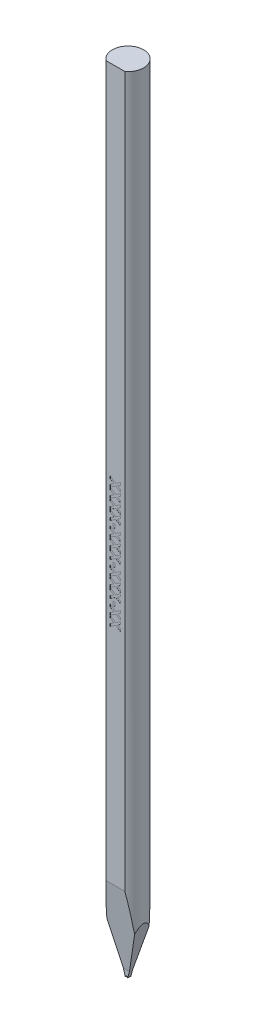
SolidWorks part; units mm, degrees
ref_plane "Ebene vorne" through (0, 0, 0) normal (0, 0, 1) x (1, 0, 0)
ref_plane "Ebene oben" through (0, 0, 0) normal (0, 1, 0) x (1, 0, 0)
ref_plane "Ebene rechts" through (0, 0, 0) normal (1, 0, 0) x (0, 0, -1)
sketch "sketch_TL_cutting" plane through (0, 0, 0) normal (0, 1, 0) x (1, 0, 0)
  circle A0 centre (0, 0) radius 1.4986
extrude "TL_cutting" add sketch "sketch_TL_cutting" along normal blind 75.9968
sketch "sketch_TDF_grinding" plane through (0, 0, 0) normal (0, 1, 0) x (1, 0, 0)
  line L0 (0, 0) -> (0, -1.2014) construction
  line L1 (-1.5086, -4.2186) -> (1.5086, -4.2186)
  line L2 (-1.5086, -4.2186) -> (-1.5086, -1.2014)
  line L3 (-1.5086, -1.2014) -> (1.5086, -1.2014)
  line L4 (1.5086, -4.2186) -> (1.5086, -1.2014)
  circle A1 centre (0, 0) radius 1.4986 construction
  point P9 (0, -4.2186)
  dimension "TD_2Offset_X" = 3.0172
  dimension "TD_2Offset_Z" = 3.0172
extrude "TDF_grinding" cut sketch "sketch_TDF_grinding" along normal through all
sketch "sketch_engraving" plane through (0, 0, 1.2014) normal (0, 0, 1) x (1, 0, 0)
  line L0 (0.8958, 75.9968) -> (-0.8958, 75.9968) construction
  line L6 (-0.8958, 0) -> (0.8958, 0) construction
  line L7 (0, 0) -> (0, 41.7982) construction
  line L8 (-0.5, 41.7982) -> (-0.5, 0) construction
  text T0 "XXXX-XXX-XXX-XX" font "Arial" height 1
  dimension "D2" = 0.5
  dimension "EngravingStart" = 34.1986
extrude "engraving" cut sketch "sketch_engraving" against normal blind 0.005
sketch "sketch_VW_VR_grinding" plane through (0, 0, 0) normal (0, 0, 1) x (1, 0, 0)
  line L0 (-1.4936, -0.01) -> (-1.4936, 0.5946)
  line L1 (1.4936, -0.01) -> (1.4936, 0.5946)
  line L2 (-1.4936, 0) -> (1.4936, 0) construction
  line L3 (-1.5086, 0.5996) -> (-1.4986, 0.5996)
  line L4 (1.4986, 0.5996) -> (1.5086, 0.5996)
  line L5 (-1.5086, 0.5996) -> (-1.5086, -0.01)
  line L6 (-1.5086, -0.01) -> (-1.4936, -0.01)
  line L7 (1.4936, -0.01) -> (1.5086, -0.01)
  line L8 (1.5086, -0.01) -> (1.5086, 0.5996)
  line L9 (-1.4986, 0.5996) -> (-1.4986, 0.5946) construction
  line L10 (-1.4936, 0.5946) -> (-1.4986, 0.5946) construction
  line L11 (1.4936, 0.5946) -> (1.4986, 0.5946) construction
  line L12 (1.4986, 0.5996) -> (1.4986, 0.5946) construction
  arc A0 (-1.4986, 0.5996) -> (-1.4936, 0.5946) centre (-1.4986, 0.5946) cw
  arc A2 (1.4936, 0.5946) -> (1.4986, 0.5996) centre (1.4986, 0.5946) cw
  dimension "D1" = 0.01
  dimension "D4" = 3.0172
extrude "VW_VR_grinding" cut sketch "sketch_VW_VR_grinding" against normal blind 1.5086 and the other way blind 1.5086
sketch "sketch_ISA_grinding" plane through (0, 0, 0) normal (0, 0, 1) x (1, 0, 0)
  line L0 (-0.1245, 0) -> (-1.5086, 5.1657)
  line L4 (1.5086, 5.1657) -> (0.1245, 0)
  line L5 (0.1245, 0) -> (-0.1245, 0)
  line L6 (0, 0) -> (0, 30.49) construction
  line L7 (-1.5086, 5.1657) -> (-1.5086, -0.01)
  line L12 (-1.5086, -0.01) -> (1.5086, -0.01)
  line L13 (1.5086, -0.01) -> (1.5086, 5.1657)
  dimension "ISA" = 30
  dimension "TD_2Offset" = 3.0172
  dimension "Offset" = 0.01
extrude "ISA_grinding" cut sketch "sketch_ISA_grinding" against normal blind 1.5086 and the other way blind 1.5086
sketch "sketch_pre_FRX_BRX" plane through (0, 0, 0) normal (1, 0, 0) x (0, 0, -1)
  line L0 (1.4986, -0.01) -> (1.4986, 3.9152) construction
  line L1 (-1.2014, -0.01) -> (-1.2014, 0.5996) construction
  line L2 (-0.1499, -0.01) -> (-0.1499, 0.5996)
  line L3 (-0.1499, 0.5996) -> (-1.5086, 0.5996)
  line L4 (-1.5086, 0.5996) -> (-1.5086, -0.01)
  line L5 (-1.5086, -0.01) -> (-0.1499, -0.01)
  line L6 (0.1499, -0.01) -> (0.1499, 0.5996)
  line L7 (0.1499, 0.5996) -> (1.5086, 0.5996)
  line L8 (1.5086, 0.5996) -> (1.5086, -0.01)
  line L9 (1.5086, -0.01) -> (0.1499, -0.01)
  dimension "D3" = 0.01
  dimension "D4" = 0.6096
  dimension "D5" = 3.0172
  dimension "D6" = 0.2997
  dimension "D2" = 0.01
  dimension "D7" = 1.6485
extrude "pre_FRX_BRX" cut sketch "sketch_pre_FRX_BRX" against normal blind 1.5086 and the other way blind 1.5086
sketch "sketch_contour_V-Groove" plane through (0, 0, 0) normal (1, 0, 0) x (0, 0, -1)
  line L0 (-1.2014, 0.0787) -> (0, 0.0787)
  line L1 (0, 0.0787) -> (1.4986, 0.0787)
  line L2 (1.4986, -0.8411) -> (1.4986, 1.3178) construction
  line L3 (-1.2014, -0.9209) -> (-1.2014, 1.9363) construction
  line L4 (-1.2014, 0) -> (1.4986, 0) construction
  line L5 (0.1499, 0) -> (0.1499, 0.0787) construction
  line L6 (-0.1499, 0) -> (-0.1499, 0.0787) construction
  dimension "D1" = 0
ref_plane "front" through (0, 0, 1.2014) normal (0, 0, 1) x (1, 0, 0)
ref_plane "back" through (0, 0, -1.4986) normal (0, 0, 1) x (1, 0, 0)
sketch "sketch_section_V-Groove" plane through (0, 0, 1.2014) normal (0, 0, 1) x (1, 0, 0)
  line L0 (-0.6199, -0.7874) -> (-0.0212, 0.0677)
  line L2 (0.0212, 0.0677) -> (0.6199, -0.7874)
  line L3 (-0.6199, -0.7874) -> (0.6199, -0.7874)
  line L4 (0, -0.7874) -> (0, 0.0787) construction
  line L5 (-0.0686, 0) -> (0.0686, 0) construction
  arc A0 (0.0212, 0.0677) -> (-0.0212, 0.0677) centre (0, 0.0529) ccw
  dimension "GA" = 70
sweep "V-Groove_EDM" cut profiles "sketch_section_V-Groove" path "sketch_contour_V-Groove"
fillet "FR_EDM" radius 0.0381 3 edges at (0.0449, 0.0339, 0.1499) (0, 0.0787, 0.1499) (-0.0449, 0.0339, 0.1499)
fillet "BR_EDM" radius 0.0381 3 edges at (0.0449, 0.0339, -0.1499) (0, 0.0787, -0.1499) (-0.0449, 0.0339, -0.1499)
sketch "sketch_FA_BA_grinding" plane through (0, 0, 0) normal (1, 0, 0) x (0, 0, -1)
  line L2 (2.4986, 17.3218) -> (2.4986, -0.1)
  line L3 (2.4986, -0.1) -> (0.1499, -0.1)
  line L5 (0.1499, -0.1) -> (0.1499, 0.6096)
  line L6 (0.1499, 0.6096) -> (2.4986, 17.3218)
  line L7 (1.4986, -0.1) -> (1.4986, 10.2064) construction
  line L8 (-1.2014, 8.0918) -> (-1.2014, -0.1) construction
  line L9 (-3.0976, 21.5836) -> (-0.1499, 0.6096)
  line L10 (-0.1499, 0.6096) -> (-0.1499, -0.1)
  line L11 (-0.1499, -0.1) -> (-3.0976, -0.1)
  line L12 (-3.0976, -0.1) -> (-3.0976, 21.5836)
  line L13 (-0.1499, 0.6096) -> (0.1499, 0.6096) construction
  dimension "D4" = 1
  dimension "D1" = 0.1
  dimension "FA" = 8
  dimension "BA" = 8
extrude "FA_BA_grinding" cut sketch "sketch_FA_BA_grinding" against normal blind 1.5086 and the other way blind 1.5086
sketch "sketch_groove_dimensions" plane through (0, 0, 0) normal (1, 0, 0) x (0, 0, -1)
  line L0 (-0.1118, 0.0787) -> (0.1118, 0.0787)
  line L1 (-0.1499, 0) -> (-0.1499, 0.1168) construction
  line L2 (1.4986, 0) -> (1.4986, 0.4166) construction
  line L3 (0.1499, 0) -> (0.1499, 0.1168) construction
  line L4 (-1.2014, 0) -> (-1.2014, 0.3999) construction
  arc A0 (0.1118, 0.0787) -> (0.1499, 0.1168) centre (0.1118, 0.1168) ccw
  arc A1 (-0.1118, 0.0787) -> (-0.1499, 0.1168) centre (-0.1118, 0.1168) cw
equation "\"_Offset\"=0.01mm"
equation "\"TL\"=75.9968mm"
equation "\"TD\"=2.9972mm"
equation "\"TDF\"=2.70002mm"
equation "\"BA\"=8deg"
equation "\"ISA\"=30deg"
equation "\"FA\"=8deg"
equation "\"GR\"=0.0254mm"
equation "\"GA\"=70deg"
equation "\"GD\"=0.07874mm"
equation "\"FL\"=0.29972mm"
equation "\"F\"=0.22352mm"
equation "\"FX\"=1.05156mm"
equation "\"B\"=0.13716mm"
equation "\"VW\"=0mm"
equation "\"cleaned_VR\"= IIF ( \"VR\" > 0 , \"VR\" , \"E\" - \"_Offset\" )"
equation "\"cleaned_VW\"= IIF ( \"VW\" > 0 , \"VW\" , \"TD\" - \"_Offset\" )"
equation "\"back_edge\"= \"TD\" / 2 - \"X\""
equation "\"side_edge_Offset\"= \"TD\" / 2 + \"_Offset\""
equation "\"TD@sketch_TL_cutting\"=\"TD\""
equation "\"TL@TL_cutting\"=\"TL\""
equation "\"TDF@sketch_TDF_grinding\"=\"TDF\""
equation "\"TD_2Offset_X@sketch_TDF_grinding\"=\"TD\"+2*\"_Offset\""
equation "\"TD_2Offset_Z@sketch_TDF_grinding\"=\"TD\"+2*\"_Offset\""
equation "\"TL_Offset\"= \"TL\" + \"_Offset\""
equation "\"ISA@sketch_ISA_grinding\"=\"ISA\""
equation "\"W@sketch_ISA_grinding\"=\"W\""
equation "\"TD_2Offset@sketch_ISA_grinding\"=\"TD\"+2*\"_Offset\""
equation "\"Offset@sketch_ISA_grinding\"=\"_Offset\""
equation "\"05TD_Offset_posZ@ISA_grinding\"=\"side_edge_Offset\""
equation "\"05TD_Offset_negZ@ISA_grinding\"=\"side_edge_Offset\""
equation "\"E\"=0.6096mm"
equation "\"cleaned_X\"= IIF ( \"X\" > 0 , \"X\" , \"TD\" / 2 - \"FL\" / 2 )"
equation "\"FR\"=0.0381mm"
equation "\"BR\"=0.0381mm"
equation "\"D1\"= \"side_edge_Offset\""
equation "\"D2\"= \"side_edge_Offset\""
equation "\"TDF@sketch_FA_BA_grinding\" = \"TDF\""
equation "\"FL@sketch_FA_BA_grinding\"=\"FL\""
equation "\"E@sketch_FA_BA_grinding\" = \"E\""
equation "\"D1@FA_BA_grinding\"=\"side_edge_Offset\""
equation "\"D2@FA_BA_grinding\"=\"side_angle_Offset\""
equation "\"10GD@sketch_section_V-Groove\" = 10 * \"GD\""
equation "\"GA@sketch_section_V-Groove\" = \"GA\""
equation "\"GD@sketch_section_V-Groove\" = \"GD\""
equation "\"B@sketch_section_V-Groove\" = \"B\""
equation "\"GD@sketch_contour_V-Groove\" = \"GD\""
equation "\"cleaned_FRX\"= IIF ( \"FRX\" > 0 , \"FRX\" , \"FR\" )"
equation "\"cleaned_BRX\"= IIF ( \"BRX\" > 0 , \"BRX\" , \"BR\" )"
equation "\"FL_groove_angle\"=0deg"
equation "\"D3@sketch_pre_FRX_BRX\" = \"_Offset\""
equation "\"D4@sketch_pre_FRX_BRX\" = \"E\""
equation "\"D5@sketch_pre_FRX_BRX\" = 2 * \"side_edge_Offset\""
equation "\"D6@sketch_pre_FRX_BRX\" = \"FL\" + ( \"FR\" - \"cleaned_FRX\" ) + ( \"BR\" - \"cleaned_BRX\" )"
equation "\"TD/2@sketch_pre_FRX_BRX\" = \"TD\" / 2"
equation "\"TDF@sketch_pre_FRX_BRX\" = \"TDF\""
equation "\"D2@sketch_pre_FRX_BRX\" = \"_Offset\""
equation "\"D1@pre_FRX_BRX\" = \"side_edge_Offset\""
equation "\"D2@pre_FRX_BRX\" = \"side_edge_Offset\""
equation "\"D1@BR_EDM\"=\"BR\""
equation "\"TD/2@sketch_FA_BA_grinding\" = \"TD\" / 2"
equation "\"TD/2@sketch_contour_V-Groove\" = \"TD\" / 2"
equation "\"TDF@sketch_contour_V-Groove\" = \"TDF\""
equation "\"D1@sketch_contour_V-Groove\"=\"FL_groove_angle\""
equation "\"FL@sketch_contour_V-Groove\"=\"FL\""
equation "\"FL/2@sketch_contour_V-Groove\" = \"FL\" / 2"
equation "\"D1@FR_EDM\"=\"FR\""
equation "\"D1@sketch_VW_VR_grinding\" = \"_Offset\""
equation "\"D4@sketch_VW_VR_grinding\" = 2 * \"side_edge_Offset\""
equation "\"VR@sketch_VW_VR_grinding\" = \"cleaned_VR\""
equation "\"VW@sketch_VW_VR_grinding\"=\"cleaned_VW\""
equation "\"D1@VW_VR_grinding\" = \"side_edge_Offset\""
equation "\"D2@VW_VR_grinding\" = \"side_edge_Offset\""
equation "\"X\"=0mm"
equation "\"VR\"=0mm"
equation "\"W\"=0.24892mm"
equation "\"VW_radius\"= \"cleaned_VW\" / 10"
equation "\"VW_radius_cleaned\"= IIF ( \"VW\" > 0 , \"VW_radius\" , \"_Offset\" / 2 )"
equation "\"D2@sketch_VW_VR_grinding\"=\"VW_radius_cleaned\""
equation "\"FRX\"=0mm"
equation "\"BRX\"=0mm"
equation "\"FA@sketch_FA_BA_grinding\" = \"FA\""
equation "\"D4@sketch_FA_BA_grinding\"=\"_Offset\"*100"
equation "\"BA@sketch_FA_BA_grinding\" = \"BA\""
equation "\"D1@sketch_groove_dimensions\" = \"TD\" / 2"
equation "\"FL@sketch_groove_dimensions\" = \"FL\""
equation "\"FR@sketch_groove_dimensions\" = \"FR\""
equation "\"BR@sketch_groove_dimensions\" = \"BR\""
equation "\"FRX@sketch_groove_dimensions\" = \"cleaned_FRX\""
equation "\"BRX@sketch_groove_dimensions\" = \"cleaned_BRX\""
equation "\"GD@sketch_groove_dimensions\" = \"GD\""
equation "\"cleaned_FX\"= IIF ( \"FX\" > 0 , \"FX\" , \"TDF\" - ( \"TD\" + \"FL\" ) / 2 )"
equation "\"D7@sketch_pre_FRX_BRX\"=\"TDF\"-\"cleaned_FX\"-(\"FR\"-\"cleaned_FRX\")"
equation "\"FX@sketch_contour_V-Groove\" = \"cleaned_FX\""
equation "\"FX@sketch_FA_BA_grinding\" = \"cleaned_FX\""
equation "\"TDF@sketch_groove_dimensions\" = \"TDF\""
equation "\"FX@sketch_groove_dimensions\" = \"cleaned_FX\""
equation "\"EngravingStart\" = \"TL\" * 0.45"
equation "\"EngravingStart@sketch_engraving\" = \"EngravingStart\""
